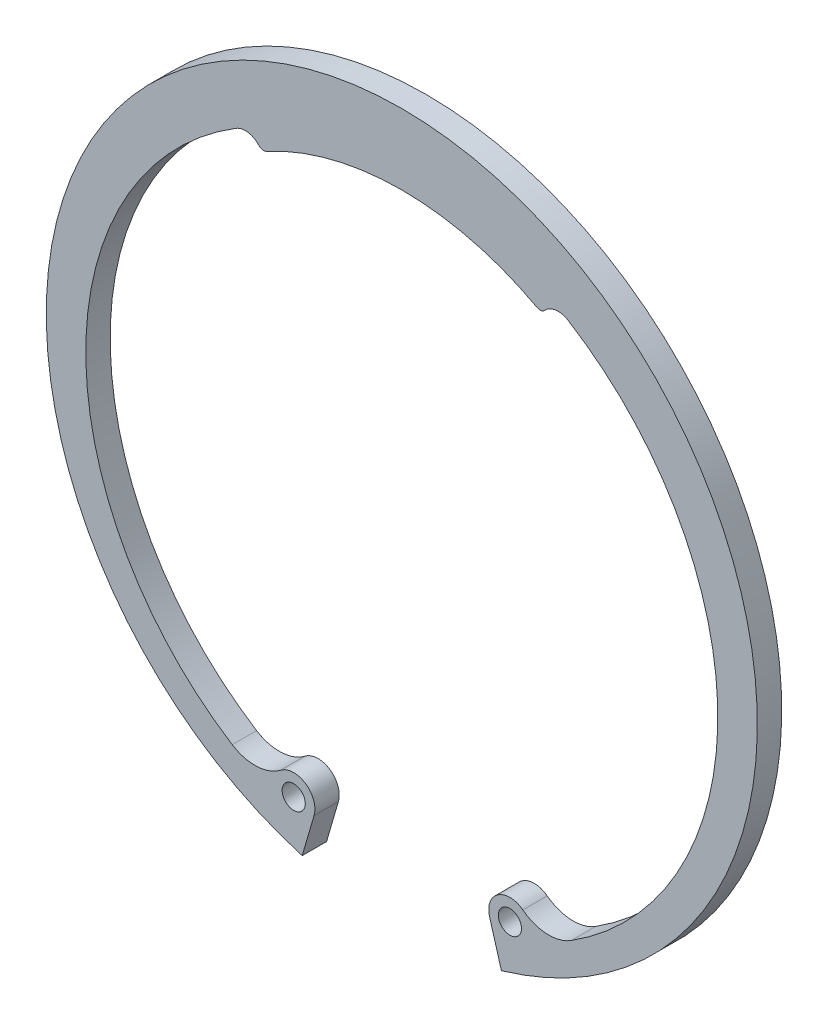
SolidWorks part; units mm, degrees
material "SPRING STEEL ASTM A 229"
ref_plane "Front Plane" through (0, 0, 0) normal (0, 0, 1) x (1, 0, 0)
ref_plane "Top Plane" through (0, 0, 0) normal (0, 1, 0) x (1, 0, 0)
ref_plane "Right Plane" through (0, 0, 0) normal (1, 0, 0) x (0, 0, -1)
sketch "Sketch1" plane through (0, 0, 0) normal (0, 0, 1) x (1, 0, 0)
  line L0 (-1.5431, 0) -> (1.5431, 0) construction
  line L1 (0, 0) -> (0, 49.65) construction
  line L2 (16.35, -56.0125) -> (14.4047, -49.3483)
  line L3 (-16.35, -56.0125) -> (-14.4047, -49.3483)
  line L4 (0, 0) -> (30.0503, -50.017) construction
  line L5 (0, 0) -> (-30.0503, -50.017) construction
  line L6 (-17.2081, -46.5507) -> (-18.2729, -50.1985) construction
  line L7 (17.5302, -47.6541) -> (17.9508, -49.0951) construction
  arc A0 (-14.4047, -49.3483) -> (-19.8607, -45.6213) centre (-17.7405, -48.3746) ccw
  arc A1 (19.8607, -45.6213) -> (14.4047, -49.3483) centre (17.7405, -48.3746) ccw
  arc A2 (27.6813, -46.0739) -> (-27.6813, -46.0739) centre (0, -2.2144) ccw construction
  arc A3 (16.35, -56.0125) -> (-16.35, -56.0125) centre (0, 0) ccw
  circle A4 centre (17.7405, -48.3746) radius 1.9
  circle A5 centre (-17.7405, -48.3746) radius 1.9
  arc A7 (27.8305, -45.9795) -> (-27.8305, -45.9795) centre (0, -2.2144) ccw
  arc A8 (-17.7405, -48.3746) -> (17.7405, -48.3746) centre (0, 0) ccw construction
  arc A9 (-27.8305, -45.9795) -> (-19.8607, -45.6213) centre (-24.1011, -40.1148) ccw
  arc A10 (19.8607, -45.6213) -> (27.8305, -45.9795) centre (24.1011, -40.1148) ccw
  dimension "GrooveDia" = 116.7
  dimension "TipRad" = 3.475
  dimension "HoleOffsetRad" = 51.525
  dimension "HoleDia" = 3.8
  dimension "FilletRad" = 6.95
  dimension "LargeRad" = 49.65
  dimension "SmallRad" = 53.75
  dimension "SmallAngle" = 61.995
  dimension "GapAngle" = 32.545
extrude "Boss-Extrude1" add sketch "Sketch1" along normal blind 4
sketch "Sketch2" plane through (0, 0, 0) normal (0, 0, -1) x (-1, 0, 0)
  line L0 (23, 40.7334) -> (24.5, 43.4985)
  line L1 (0, 0) -> (0, 41.707) construction
  line L2 (-23, 40.7334) -> (-24.5, 43.4985)
  arc A0 (23, 40.7334) -> (-23, 40.7334) centre (0, 0) ccw
  arc A4 (27.8305, -45.9795) -> (-27.8305, -45.9795) centre (0, -2.2144) ccw construction
  arc A5 (24.5, 43.4985) -> (-24.5, 43.4985) centre (0, -2.2144) ccw
  dimension "D1" = 46.7783
  dimension "D2" = 46
  dimension "D3" = 49
extrude "Boss-Extrude2" add sketch "Sketch2" against normal up to surface (4 mm away) up to face at (19.6405, -48.3746, 4)
fillet "Fillet1" radius 3 2 edges at (-24.5, 43.4985, 2) (24.5, 43.4985, 2)
fillet "Fillet2" radius 1 2 edges at (-23, 40.7334, 2) (23, 40.7334, 2)
